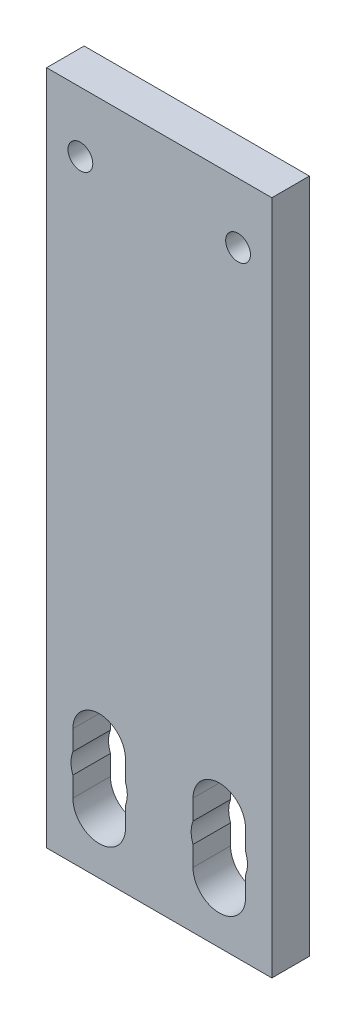
SolidWorks part; units mm, degrees
material "1.4301 (X5CrNi18-10)"
ref_plane "Ebene1" through (0, 0, 0) normal (0, 0, 1) x (1, 0, 0)
ref_plane "Ebene2" through (0, 0, 0) normal (0, 1, 0) x (1, 0, 0)
ref_plane "Ebene3" through (0, 0, 0) normal (1, 0, 0) x (0, 0, -1)
sketch "Skizze2" plane through (0, 0, 0) normal (0, 0, 1) x (1, 0, 0)
  line L1 (-15, 0) -> (15, 0)
  line L2 (-15, 0) -> (-15, 90)
  line L3 (-15, 90) -> (15, 90)
  line L4 (15, 0) -> (15, 90)
  dimension "D1" = 30
  dimension "D2" = 90
extrude "Aufsatz-Linear austragen2" add sketch "Skizze2" along normal mid plane 5
sketch "Skizze1" plane through (0, 0, 0) normal (0, 0, 1) x (1, 0, 0)
  line L0 (8, 15.5) -> (8, 11.5) construction
  line L1 (-15, 0) -> (15, 0) construction
  line L5 (-11.5, 12.8463) -> (-11.5, 15.5)
  line L6 (-11.5, 7.5) -> (-11.5, 10.1537)
  line L7 (-4.5, 12.8463) -> (-4.5, 15.5)
  line L8 (-4.5, 7.5) -> (-4.5, 10.1537)
  line L9 (4.5, 12.8463) -> (4.5, 15.5)
  line L10 (4.5, 7.5) -> (4.5, 10.1537)
  line L11 (11.5, 12.8463) -> (11.5, 15.5)
  line L12 (11.5, 7.5) -> (11.5, 10.1537)
  line L13 (8, 11.5) -> (8, 7.5) construction
  line L14 (0, 0) -> (0, 99) construction
  line L15 (-8, 7.5) -> (0, 7.5) construction
  line L16 (0, 7.5) -> (8, 7.5) construction
  arc A0 (-4.5, 15.5) -> (-11.5, 15.5) centre (-8, 15.5) ccw
  arc A1 (-11.5, 7.5) -> (-4.5, 7.5) centre (-8, 7.5) ccw
  arc A2 (11.5, 15.5) -> (4.5, 15.5) centre (8, 15.5) ccw
  arc A3 (4.5, 7.5) -> (11.5, 7.5) centre (8, 7.5) ccw
  arc A6 (-11.5, 12.8463) -> (-11.5, 10.1537) centre (-8, 11.5) ccw
  arc A7 (4.5, 12.8463) -> (4.5, 10.1537) centre (8, 11.5) ccw
  arc A8 (-4.5, 10.1537) -> (-4.5, 12.8463) centre (-8, 11.5) ccw
  arc A9 (11.5, 10.1537) -> (11.5, 12.8463) centre (8, 11.5) ccw
  dimension "D3" = 3.5
  dimension "D4" = 15
  dimension "D7" = 16
  dimension "D12" = 3.75
  dimension "D2" = 7.5
extrude "Schnitt-Linear austragen1" cut sketch "Skizze1" against normal mid plane 10
hole_wizard "M4 Gewindebohrung1" positions "Skizze5" profile "Skizze4" tap size "M4" standard "Gabler-Normteile"
sketch "Skizze5" plane through (0, 0, 2.5) normal (0, 0, 1) x (1, 0, 0)
  line L0 (0, 0) -> (0, 82) construction
  line L1 (-15, 0) -> (15, 0) construction
  line L4 (-10.5, 82) -> (10.5, 82) construction
  point P0 (-10.5, 82)
  point P2 (10.5, 82)
  dimension "D1" = 82
  dimension "D2" = 21
sketch "Skizze4" plane through (-10.5, 82, 2.5) normal (1, 0, 0) x (0, -1, 0)
  line L0 (0, 0) -> (0, 12.4914)
  line L1 (0, 12.4914) -> (1.65, 11.5)
  line L2 (1.65, 11.5) -> (1.65, 0)
  line L5 (1.65, 0) -> (0, 0)
  line L10 (0, 12.4914) -> (-1.65, 11.5) construction
  line L11 (0, -6.35) -> (0, 107.95) construction
  dimension "Bohrerdurchmesser" = 3.3
  dimension "Bohrungstiefe" = 11.5
  dimension "Spitzenwinkel" = 118
cosmetic thread "Bohrungsgewinde1" parameters "D1"=5, "D2"=4
cosmetic thread "Bohrungsgewinde2" parameters "D1"=5, "D2"=4
